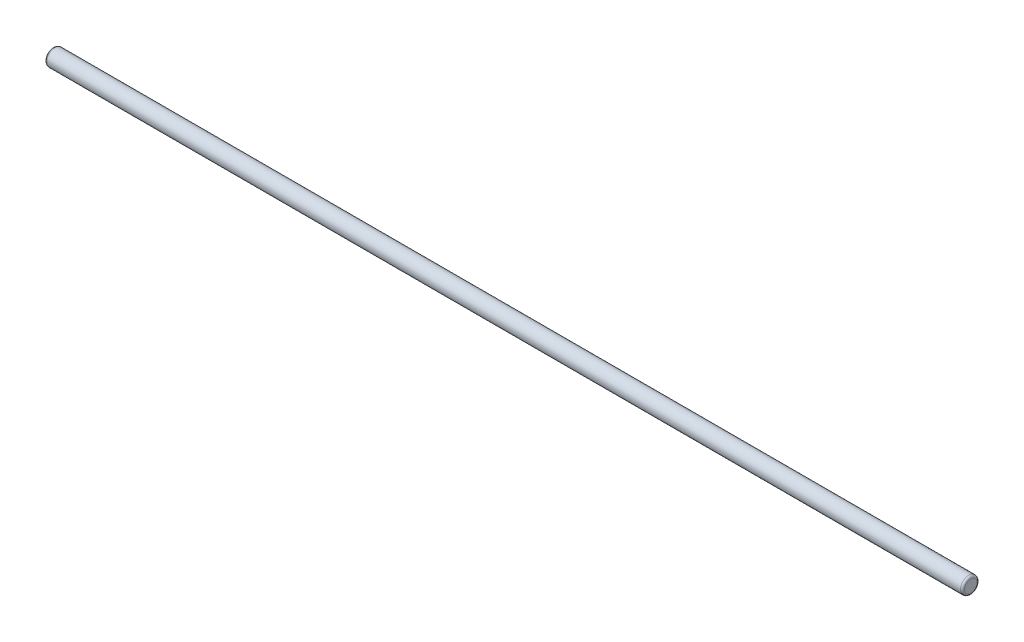
SolidWorks part; units mm, degrees
ref_plane "Front Plane" through (0, 0, 0) normal (0, 0, 1) x (1, 0, 0)
ref_plane "Top Plane" through (0, 0, 0) normal (0, 1, 0) x (1, 0, 0)
ref_plane "Right Plane" through (0, 0, 0) normal (1, 0, 0) x (0, 0, -1)
sketch "ProfileSketch1" plane through (0, 0, 0) normal (1, 0, 0) x (0, 0, -1)
  circle A0 centre (0, 0) radius 4
  dimension "D1" = 8
extrude "ProfileBoss-Extrude1" add sketch "ProfileSketch1" along normal blind 440
fillet "Fillet1" radius 1 2 edges at (0, 0, -4) (440, 0, -4)
equation "\"RodShaft8mmDiameter\"= 8mm"
equation "\"RodShaft440mmLength\"= 440mm"
equation "\"D1@ProfileBoss-Extrude1\" = \"RodShaft440mmLength\""
equation "\"D1@ProfileSketch1\"=\"RodShaft8mmDiameter\""
